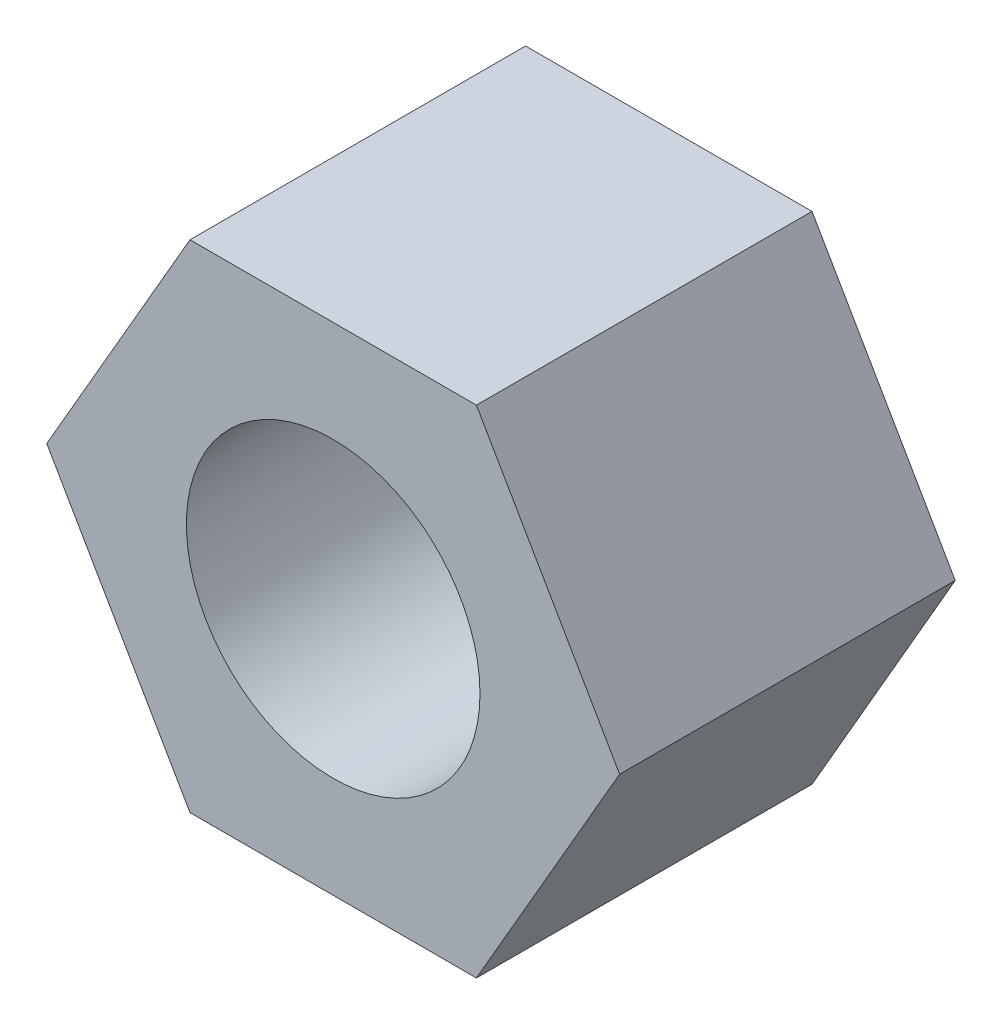
SolidWorks part; units mm, degrees
ref_plane "Front Plane" through (0, 0, 0) normal (0, 0, 1) x (1, 0, 0)
ref_plane "Top Plane" through (0, 0, 0) normal (0, 1, 0) x (1, 0, 0)
ref_plane "Right Plane" through (0, 0, 0) normal (1, 0, 0) x (0, 0, -1)
sketch "S01 - Hexagon and nominal thread envelope" plane through (0, 0, 0) normal (0, 0, 1) x (1, 0, 0)
  line L0 (9.815, 0) -> (4.9075, 8.5)
  line L1 (4.9075, 8.5) -> (-4.9075, 8.5)
  line L2 (-4.9075, 8.5) -> (-9.815, 0)
  line L3 (-9.815, 0) -> (-4.9075, -8.5)
  line L4 (-4.9075, -8.5) -> (4.9075, -8.5)
  line L5 (4.9075, -8.5) -> (9.815, 0)
  circle A0 centre (0, 0) radius 5.03
  dimension "D1" = 10.06
  dimension "D2" = 4.9075
  dimension "D3" = 9.815
  dimension "D4" = 4.9075
  dimension "D5" = 9.815
  dimension "D6" = 8.5
  dimension "D7" = 8.5
extrude "01 - Hexagon and nominal thread envelope" add sketch "S01 - Hexagon and nominal thread envelope" along normal blind 11.5
